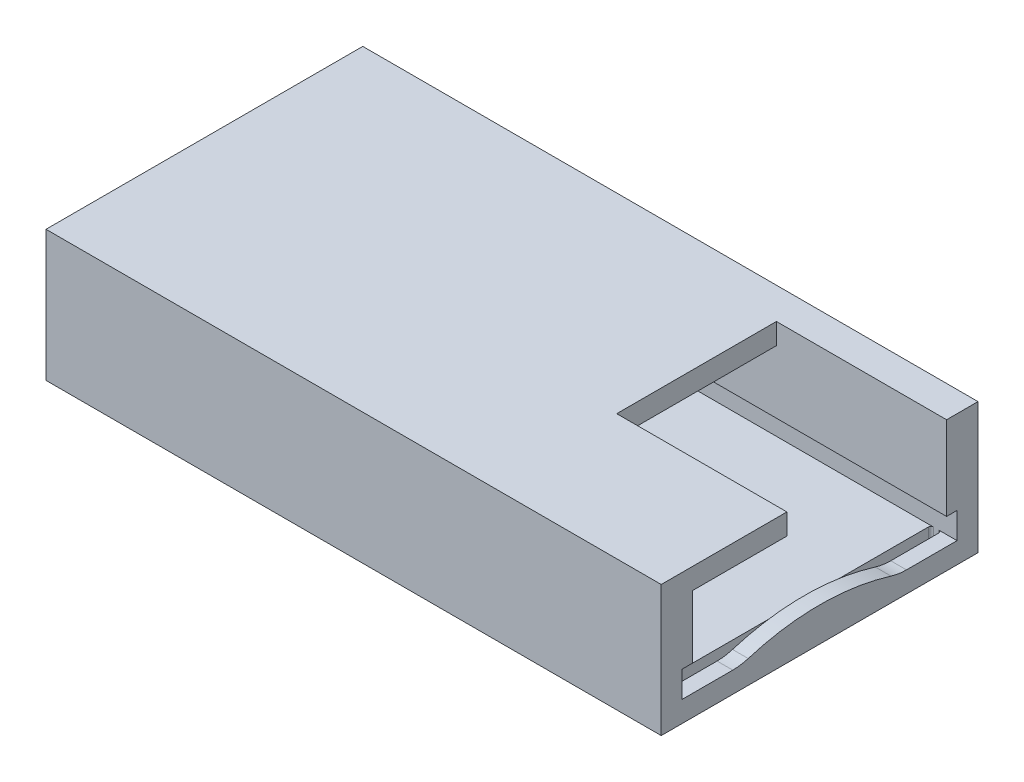
SolidWorks part; units mm, degrees
ref_plane "Alzado" through (0, 0, 0) normal (0, 0, 1) x (1, 0, 0)
ref_plane "Planta" through (0, 0, 0) normal (0, 1, 0) x (1, 0, 0)
ref_plane "Vista lateral" through (0, 0, 0) normal (1, 0, 0) x (0, 0, -1)
sketch "Croquis1" plane through (0, 0, 0) normal (0, 1, 0) x (1, 0, 0)
  line L1 (22.5, -12.1) -> (-22.5, -12.1)
  line L2 (22.5, -12.1) -> (22.5, 12.1)
  line L3 (22.5, 12.1) -> (-22.5, 12.1)
  line L4 (-22.5, -12.1) -> (-22.5, 12.1)
  line L5 (22.5, -12.1) -> (-22.5, 12.1) construction
  line L6 (22.5, 12.1) -> (-22.5, -12.1) construction
  point P0 (0, 0)
  dimension "D1" = 24.2
  dimension "D2" = 45
extrude "Saliente-Extruir1" add sketch "Croquis1" along normal blind 10
sketch "Croquis2" plane through (22.5, 0, 0) normal (1, 0, 0) x (0, 0, -1)
  line L0 (-12.1, 0) -> (12.1, 0) construction
  line L1 (10.5, 1.6) -> (-10.5, 1.6)
  line L2 (10.5, 1.6) -> (10.5, 3.6)
  line L3 (10.5, 3.6) -> (9.7, 3.6)
  line L4 (-10.5, 1.6) -> (-10.5, 3.6)
  line L5 (10.5, 1.6) -> (-10.5, 3.6) construction
  line L6 (10.5, 3.6) -> (-10.5, 1.6) construction
  line L7 (9.7, 3.6) -> (9.7, 8.4)
  line L8 (9.7, 8.4) -> (-9.7, 8.4)
  line L9 (-12.1, 10) -> (12.1, 10) construction
  line L10 (-12.1, 10) -> (-12.1, 0) construction
  line L13 (-9.7, 8.4) -> (-9.7, 3.6)
  line L14 (-9.7, 3.6) -> (-10.5, 3.6)
  point P5 (0, 1.6)
  dimension "D1" = 21
  dimension "D2" = 2
  dimension "D3" = 1.6
  dimension "D4" = 1.6
  dimension "D5" = 1.6
  dimension "D6" = 0.8
  dimension "D7" = 0.8
extrude "Cortar-Extruir2" cut sketch "Croquis2" against normal blind 43
sketch "Croquis4" plane through (22.5, 0, 0) normal (1, 0, 0) x (0, 0, -1)
  line L1 (-2.5, 3.6) -> (7, 3.6)
  line L2 (-2.5, 3.6) -> (-2.5, 8.4)
  line L3 (-2.5, 8.4) -> (7, 8.4)
  line L4 (7, 3.6) -> (7, 8.4)
  line L6 (-12.1, 10) -> (-12.1, 0) construction
  line L7 (10.5, 1.6) -> (10.5, 3.6) construction
  line L8 (-9.7, 3.6) -> (-10.5, 3.6) construction
  line L10 (9.7, 8.4) -> (-9.7, 8.4) construction
  point P4 (0, 0)
  point P7 (-2.5, 6)
  dimension "D2" = 9.5
  dimension "D3" = 13
  dimension "D4" = 19.1
extrude "Cortar-Extruir3" cut sketch "Croquis4" against normal through all
sketch "Croquis5" plane through (22.5, 0, 0) normal (1, 0, 0) x (0, 0, -1)
  line L0 (9.7, 8.4) -> (9.7, 10)
  line L1 (-12.1, 10) -> (12.1, 10) construction
  line L2 (9.7, 10) -> (-2.5, 10)
  line L3 (-2.5, 10) -> (-2.5, 8.4)
  line L4 (9.7, 8.4) -> (-9.7, 8.4) construction
  line L5 (-2.5, 8.4) -> (9.7, 8.4)
  line L6 (10.5, 1.6) -> (10.5, 3.6) construction
  dimension "D1" = 13
extrude "Cortar-Extruir4" cut sketch "Croquis5" against normal blind 11
sketch "Croquis6" plane through (22.5, 0, 0) normal (1, 0, 0) x (0, 0, -1)
  line L0 (-12.1, 0) -> (12.1, 0) construction
  line L1 (-12.1, 10) -> (12.1, 10)
  line L2 (-12.1, 10) -> (-12.1, 0)
  line L3 (9.7, 10) -> (9.7, 3.6)
  line L4 (12.1, 10) -> (12.1, 0)
  line L5 (12.1, 10) -> (12.1, 0) construction
  line L6 (-2.5, 10) -> (-2.5, 8.4)
  line L7 (-2.5, 8.4) -> (-9.7, 8.4)
  line L8 (-9.7, 8.4) -> (-9.7, 3.6)
  line L9 (-9.7, 3.6) -> (-10.5, 3.6)
  line L10 (-10.5, 3.6) -> (-10.5, 0)
  line L11 (-10.5, 0) -> (-12.1, 0)
  line L13 (9.7, 3.6) -> (10.5, 3.6)
  line L14 (10.5, 3.6) -> (10.5, 0)
  line L15 (10.5, 0) -> (12.1, 0)
  line M3 (-9.7, 8.4) -> (-2.5, 8.4)
  line M4 (-2.5, 8.4) -> (-2.5, 10)
  line M5 (-2.5, 10) -> (-12.1, 10)
  line M6 (-12.1, 10) -> (-12.1, 0)
  line M7 (-12.1, 0) -> (12.1, 0)
  line M8 (12.1, 0) -> (12.1, 10)
  line M9 (12.1, 10) -> (9.7, 10)
  line M10 (9.7, 10) -> (9.7, 3.6)
  line M11 (9.7, 3.6) -> (10.5, 3.6)
  line M12 (10.5, 3.6) -> (10.5, 1.6)
  line M14 (-10.5, 1.6) -> (-10.5, 3.6)
  line M15 (-10.5, 3.6) -> (-9.7, 3.6)
  line M16 (-9.7, 3.6) -> (-9.7, 8.4)
extrude "Saliente-Extruir2" add sketch "Croquis6" along normal blind 2 contours L10 M14 M15 M16 M3 M4 M5 M6 M7 | L14 M12 M7 M8 M9 M10 M11
sketch "Croquis7" plane through (24.5, 0, 0) normal (1, 0, 0) x (0, 0, -1)
  line L0 (-10.5, 0) -> (10.5, 0)
  line L1 (10.5, 0) -> (10.5, 1.6)
  line L2 (10.5, 1.6) -> (6, 1.6)
  line L3 (0, 1.6) -> (0, 2.6) construction
  line L4 (10.5, 1.6) -> (-10.5, 3.6) construction
  line L6 (-6, 1.6) -> (-10.5, 1.6)
  line L7 (10.5, 1.6) -> (-10.5, 1.6) construction
  line L8 (-10.5, 1.6) -> (-10.5, 0)
  circle A0 centre (0, 1.6) radius 6 construction
  arc A1 (6, 1.6) -> (-6, 1.6) centre (0, -15.9) ccw
  point P12 (-6, 1.6)
  point P13 (6, 1.6)
  dimension "D1" = 12
extrude "Saliente-Extruir3" add sketch "Croquis7" against normal blind 1.2
fillet "Redondeo1" radius 4 2 edges at (23.9, 1.6, -6) (23.9, 1.6, 6)
fillet "Redondeo2" radius 0.2 4 edges at (23.3, 0.8, 10.5) (22.5, 0.8, 10.5) (23.3, 0.8, -10.5) (22.5, 0.8, -10.5)
